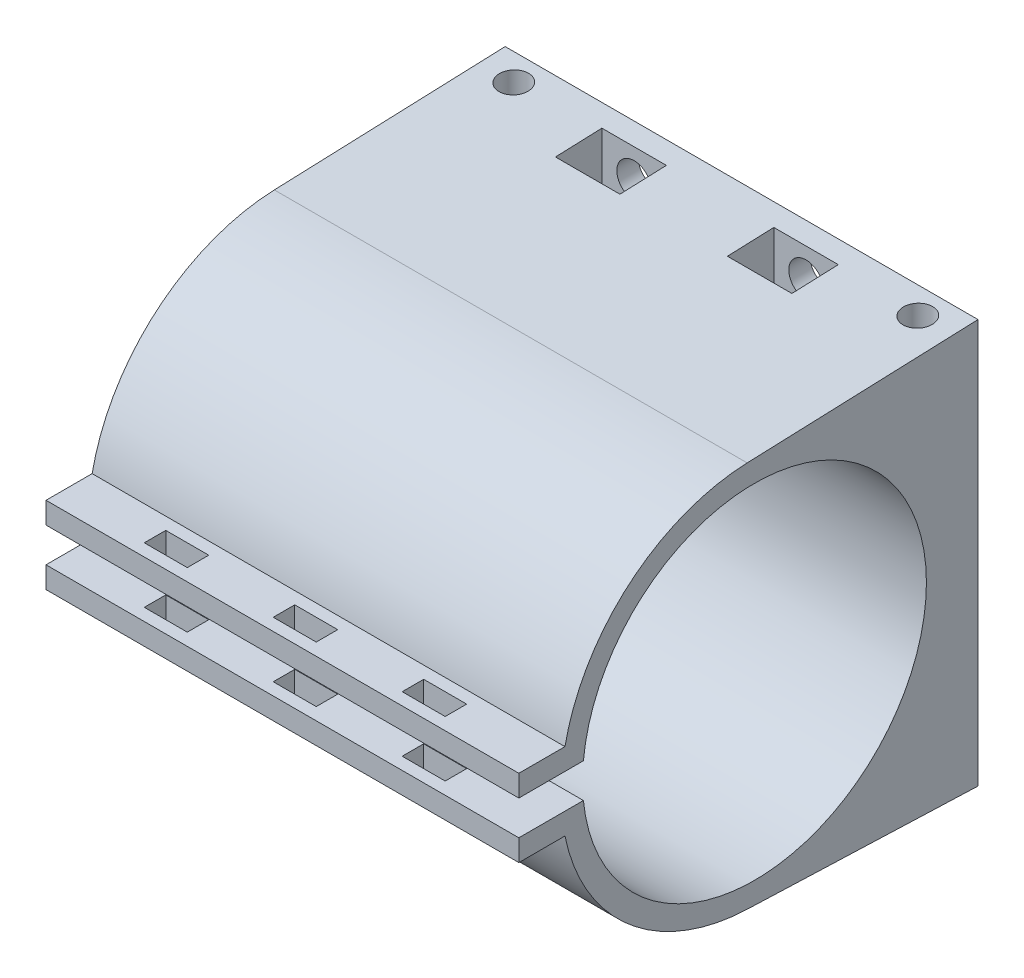
SolidWorks part; units mm, degrees
ref_plane "Front Plane" through (0, 0, 0) normal (0, 0, 1) x (1, 0, 0)
ref_plane "Top Plane" through (0, 0, 0) normal (0, 1, 0) x (1, 0, 0)
ref_plane "Right Plane" through (0, 0, 0) normal (1, 0, 0) x (0, 0, -1)
sketch "Sketch1" plane through (0, 0, 0) normal (1, 0, 0) x (0, 0, -1)
  circle A0 centre (0, 0) radius 25.4
  circle A1 centre (0, 0) radius 28.575
  dimension "D1" = 50.8
  dimension "D2" = 57.15
extrude "Boss-Extrude1" add sketch "Sketch1" along normal blind 69.85
sketch "Sketch2" plane through (69.85, 0, 0) normal (1, 0, 0) x (0, 0, -1)
  line L0 (33.02, -29.845) -> (33.02, 29.845)
  line L1 (33.02, 29.845) -> (-1.0806, 28.5546)
  line L2 (33.02, -29.845) -> (-1.0806, -28.5546)
  line L3 (25.4, 0) -> (25.4, 26.6954) construction
  circle A1 centre (0, 0) radius 28.575 construction
  arc A2 (-1.0806, 28.5546) -> (-1.0806, -28.5546) centre (0, 0) cw
  circle A3 centre (0, 0) radius 25.4 construction
  point P3 (33.02, 30.1186)
  point P11 (28.575, 20.0214)
  point P16 (0, 0)
  point P17 (0, 0)
  point P18 (28.575, 0)
  point P19 (0, 0)
  point P20 (32.7662, 0)
  circle M4 centre (0, 0) radius 28.575
  dimension "D1" = 59.69
  dimension "D4" = 33.02
extrude "Boss-Extrude2" add sketch "Sketch2" against normal through all contours L2 L0 M4 | L0 L1 M4
sketch "Sketch4" plane through (0, 0, -33.02) normal (0, 0, -1) x (-1, 0, 0)
  line L0 (-47.625, 25.4) -> (-47.625, -25.4) construction
  line L1 (-69.85, -29.845) -> (-69.85, 29.845) construction
  circle A0 centre (-47.625, 25.4) radius 2.5527
  circle A1 centre (-22.225, 25.4) radius 2.5527
  circle A2 centre (-34.925, -25.4) radius 2.5527
  point P7 (-47.625, 0)
  dimension "D4" = 5.1054
  dimension "D1" = 12.7
  dimension "D2" = 12.7
  dimension "D3" = 50.8
  dimension "D5" = 34.925
extrude "Cut-Extrude1" cut sketch "Sketch4" against normal blind 16.256
ref_plane "Plane1" through (0, 0, -29.845) normal (0, 0, -1) x (-1, 0, 0)
sketch "Sketch7" plane through (0, 0, -29.845) normal (0, 0, -1) x (-1, 0, 0)
  line L1 (-42.8625, 22.6504) -> (-42.8625, 29.845)
  line L2 (-45.799, 29.845) -> (-47.625, 30.8993)
  line L3 (-47.625, 30.8993) -> (-49.451, 29.845)
  line L4 (-52.3875, 29.845) -> (-52.3875, 22.6504)
  line L5 (-52.3875, 22.6504) -> (-47.625, 19.9007)
  line L6 (-47.625, 19.9007) -> (-42.8625, 22.6504)
  line L7 (-17.4625, 22.6504) -> (-17.4625, 29.845)
  line L8 (-20.399, 29.845) -> (-22.225, 30.8993)
  line L9 (-22.225, 30.8993) -> (-24.051, 29.845)
  line L10 (-26.9875, 29.845) -> (-26.9875, 22.6504)
  line L11 (-26.9875, 22.6504) -> (-22.225, 19.9007)
  line L12 (-22.225, 19.9007) -> (-17.4625, 22.6504)
  line L13 (-30.1625, -22.6504) -> (-34.925, -19.9007)
  line L14 (-34.925, -19.9007) -> (-39.6875, -22.6504)
  line L15 (-39.6875, -22.6504) -> (-39.6875, -29.845)
  line L16 (-36.751, -29.845) -> (-34.925, -30.8993)
  line L17 (-34.925, -30.8993) -> (-33.099, -29.845)
  line L18 (-30.1625, -29.845) -> (-30.1625, -22.6504)
  line L22 (-69.85, 29.845) -> (-69.85, -29.845)
  line L23 (-69.85, -29.845) -> (0, -29.845)
  line L24 (0, -29.845) -> (0, 29.845)
  line L25 (0, 29.845) -> (-69.85, 29.845)
  line L26 (-69.85, 29.845) -> (-69.85, -29.845)
  line L27 (-69.85, -29.845) -> (0, -29.845)
  line L28 (0, -29.845) -> (0, 29.845)
  line L29 (0, 29.845) -> (-69.85, 29.845)
  circle A0 centre (-47.625, 25.4) radius 4.7625 construction
  circle A1 centre (-22.225, 25.4) radius 4.7625 construction
  circle A2 centre (-34.925, -25.4) radius 4.7625 construction
  dimension "D1" = 9.525
  dimension "D2" = 0
extrude "Cut-Extrude2" cut sketch "Sketch7" against normal blind 6.858 contours L1 L29 L4 L5 L6 | L7 L29 L10 L11 L12 | L15 L27 L18 L13 L14
sketch "Sketch9" plane through (69.85, 0, 0) normal (1, 0, 0) x (0, 0, -1)
  line L1 (-20.4251, -2.54) -> (-30.3749, -2.54)
  line L2 (-20.4251, -2.54) -> (-20.4251, 2.54)
  line L3 (-20.4251, 2.54) -> (-30.3749, 2.54)
  line L4 (-30.3749, -2.54) -> (-30.3749, 2.54)
  line L5 (-20.4251, -2.54) -> (-30.3749, 2.54) construction
  line L6 (-20.4251, 2.54) -> (-30.3749, -2.54) construction
  circle A0 centre (0, 0) radius 25.4 construction
  point P0 (-25.4, 0)
  dimension "D1" = 5.08
extrude "Cut-Extrude3" cut sketch "Sketch9" against normal through all
sketch "Sketch10" plane through (69.85, 0, 0) normal (1, 0, 0) x (0, 0, -1)
  line L0 (-28.4619, 2.54) -> (-34.8119, 2.54)
  line L1 (-34.8119, 2.54) -> (-34.8119, 5.715)
  line L2 (-34.8119, 5.715) -> (-27.9977, 5.715)
  line L3 (0, 0) -> (-3.8306, 0) construction
  line L4 (-34.8119, -5.715) -> (-27.9977, -5.715)
  line L5 (-34.8119, -2.54) -> (-34.8119, -5.715)
  line L6 (-28.4619, -2.54) -> (-34.8119, -2.54)
  line L10 (-28.4619, 2.54) -> (-25.2727, 2.54)
  line L11 (-25.2727, -2.54) -> (-28.4619, -2.54)
  line L12 (-1.0806, -28.5546) -> (33.02, -29.845)
  line L14 (-1.0806, -28.5546) -> (33.02, -29.845)
  line L17 (-28.4619, 2.54) -> (-25.2727, 2.54)
  line L18 (-25.2727, -2.54) -> (-28.4619, -2.54)
  line L31 (33.02, -29.845) -> (33.02, 29.845)
  line L33 (33.02, -29.845) -> (33.02, 29.845)
  line L36 (33.02, 29.845) -> (-1.0806, 28.5546)
  line L37 (33.02, 29.845) -> (-1.0806, 28.5546)
  arc A0 (-1.0806, 28.5546) -> (-28.4619, 2.54) centre (0, 0) ccw construction
  arc A4 (-25.2727, -2.54) -> (-25.2727, 2.54) centre (0, 0) ccw
  arc A6 (-25.2727, -2.54) -> (-25.2727, 2.54) centre (0, 0) ccw
  arc A11 (-28.4619, -2.54) -> (-1.0806, -28.5546) centre (0, 0) ccw
  arc A13 (-28.4619, -2.54) -> (-1.0806, -28.5546) centre (0, 0) ccw
  arc A14 (-1.0806, 28.5546) -> (-28.4619, 2.54) centre (0, 0) ccw
  arc A15 (-1.0806, 28.5546) -> (-28.4619, 2.54) centre (0, 0) ccw
  arc M17 (-28.4619, -2.54) -> (-1.0806, -28.5546) centre (0, 0) ccw
  arc M23 (-1.0806, 28.5546) -> (-28.4619, 2.54) centre (0, 0) ccw
  dimension "D2" = 3.175
  dimension "D3" = 6.35
  dimension "D1" = 0
extrude "Boss-Extrude3" add sketch "Sketch10" against normal through all contours L2 L1 L0 M23 | L6 L5 L4 M17
sketch "Sketch11" plane through (0, 5.715, 0) normal (0, 1, 0) x (1, 0, 0)
  line L0 (69.85, -34.8119) -> (69.85, -27.9977) construction
  line L1 (50.8, -29.8173) -> (57.15, -29.8173)
  line L2 (50.8, -29.8173) -> (50.8, -32.9923)
  line L3 (50.8, -32.9923) -> (57.15, -32.9923)
  line L4 (57.15, -29.8173) -> (57.15, -32.9923)
  line L5 (31.75, -29.8173) -> (38.1, -29.8173)
  line L6 (31.75, -29.8173) -> (31.75, -32.9923)
  line L7 (38.1, -29.8173) -> (38.1, -32.9923)
  line L8 (31.75, -32.9923) -> (38.1, -32.9923)
  line L9 (12.7, -29.8173) -> (19.05, -29.8173)
  line L10 (12.7, -29.8173) -> (12.7, -32.9923)
  line L11 (19.05, -29.8173) -> (19.05, -32.9923)
  line L12 (12.7, -32.9923) -> (19.05, -32.9923)
  point P4 (57.15, -31.4048)
  point P5 (69.85, -31.4048)
  dimension "D1" = 3.175
  dimension "D2" = 6.35
  dimension "D3" = 12.7
  dimension "D5" = 12.7
  dimension "D4" = 3
extrude "Cut-Extrude4" cut sketch "Sketch11" against normal through all
sketch "Sketch13" plane through (0, 0, 0.5405) normal (0, -1, 0) x (1, 0, 0)
  line L0 (0, -33.5605) -> (69.85, -33.5605) construction
  line L1 (69.85, -33.5605) -> (69.85, 0.5401) construction
  line L2 (0, -33.5605) -> (0, 0.5401) construction
  circle A0 centre (64.77, -29.7505) radius 2.1844
  circle A1 centre (5.08, -29.7505) radius 2.1844
  dimension "D1" = 4.3688
  dimension "D4" = 3.81
  dimension "D2" = 3.81
  dimension "D3" = 5.08
  dimension "D5" = 5.08
extrude "Cut-Extrude5" cut sketch "Sketch13" against normal through all both and the other way through all
